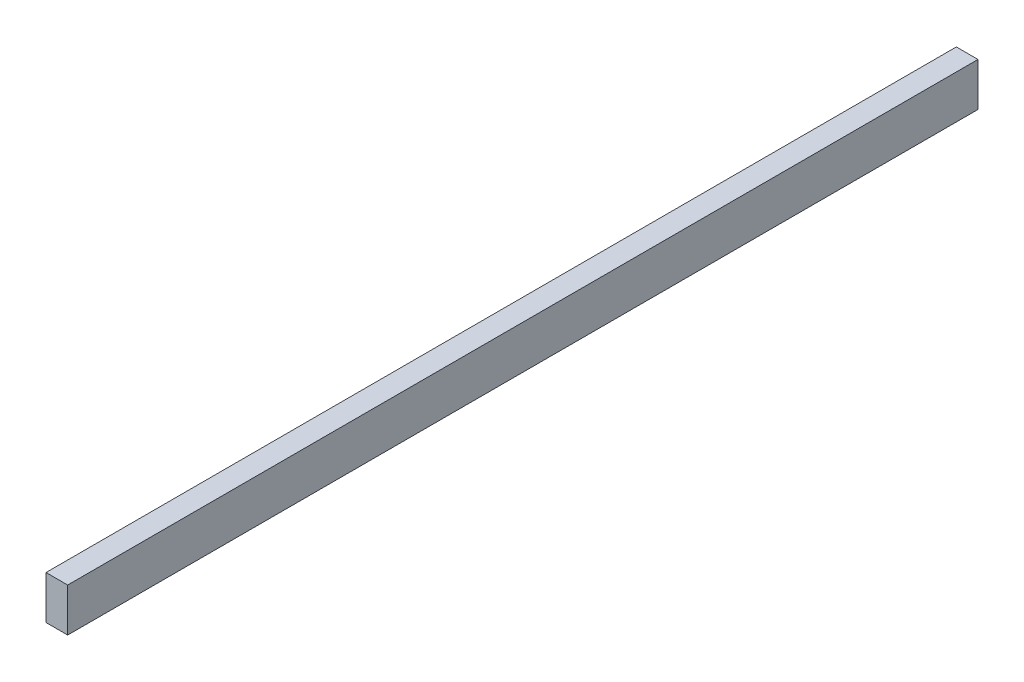
SolidWorks part; units mm, degrees
ref_plane "Front Plane" through (0, 0, 0) normal (0, 0, 1) x (1, 0, 0)
ref_plane "Top Plane" through (0, 0, 0) normal (0, 1, 0) x (1, 0, 0)
ref_plane "Right Plane" through (0, 0, 0) normal (1, 0, 0) x (0, 0, -1)
sketch "Sketch1" plane through (0, 0, 0) normal (0, 0, 1) x (1, 0, 0)
  line L0 (-12.7, 25.4) -> (12.7, 25.4)
  line L1 (-12.7, 25.4) -> (-12.7, -25.4)
  line L2 (-12.7, -25.4) -> (12.7, -25.4)
  line L3 (12.7, 25.4) -> (12.7, -25.4)
  line L4 (-12.7, 25.4) -> (12.7, -25.4) construction
  point P4 (12.0112, 25.4717)
  point P5 (0, 0)
  dimension "D1" = 25.4
  dimension "D2" = 50.8
extrude "Boss-Extrude1" add sketch "Sketch1" along normal blind 1066.8
sketch "Sketch2" plane through (0, 0, 1066.8) normal (0, 0, 1) x (1, 0, 0)
  line L0 (-6.8478, 24.8291) -> (-11.9347, 24.8291)
  line L1 (-11.9347, 24.8291) -> (-11.9347, 19.7422)
  line L2 (9.2759, 0.3342) -> (9.3949, 0.4532)
  line L3 (9.2759, -12.1118) -> (9.2759, 0.3342)
  line L4 (9.3866, -12.2225) -> (9.2759, -12.1118)
  line L5 (9.2433, -12.3658) -> (9.3866, -12.2225)
  line L6 (9.2433, -17.9626) -> (9.2433, -12.3658)
  line L7 (4.6078, -23.9228) -> (4.6078, -22.2178)
  line L8 (-5.1712, -23.9228) -> (4.6078, -23.9228)
  line L9 (-5.1712, -22.2178) -> (-5.1712, -23.9228)
  line L10 (-9.8067, -12.3658) -> (-9.8067, -17.9626)
  line L11 (-9.9337, -12.2388) -> (-9.8067, -12.3658)
  line L12 (-9.8067, -12.1118) -> (-9.9337, -12.2388)
  line L13 (-9.8067, 0.3342) -> (-9.8067, -12.1118)
  line L14 (-9.9337, 0.4612) -> (-9.8067, 0.3342)
  line L15 (-9.8067, 0.5882) -> (-9.9337, 0.4612)
  line L16 (-9.8067, 13.0342) -> (-9.8067, 0.5882)
  line L17 (-9.9174, 13.1449) -> (-9.8067, 13.0342)
  line L18 (-9.7741, 13.2882) -> (-9.9174, 13.1449)
  line L19 (-9.7741, 18.885) -> (-9.7741, 13.2882)
  line L20 (-5.1712, 24.8291) -> (-5.1712, 23.1241)
  line L21 (4.6078, 24.8291) -> (-5.1712, 24.8291)
  line L22 (4.6078, 23.1241) -> (4.6078, 24.8291)
  line L23 (9.1633, 13.1857) -> (9.1633, 18.7825)
  line L24 (9.3021, 13.0443) -> (9.1633, 13.1857)
  line L25 (9.2759, 13.0181) -> (9.3021, 13.0443)
  line L26 (9.2759, 0.5721) -> (9.2759, 13.0181)
  line L27 (9.3949, 0.4532) -> (9.2759, 0.5721)
  arc A0 (4.6078, -22.2178) -> (9.2433, -17.9626) centre (-0.2817, -12.2388) ccw
  arc A1 (-9.8067, -17.9626) -> (-5.1712, -22.2178) centre (-0.2817, -12.2388) ccw
  arc A2 (-5.1712, 23.1241) -> (-9.7741, 18.885) centre (-0.2491, 13.1612) ccw
  arc A3 (9.1633, 18.7825) -> (4.6078, 23.1241) centre (-0.4673, 13.2382) ccw
  arc A4 (-6.1551, 24.1371) -> (-6.8478, 24.8291) centre (-6.8478, 24.1364) ccw
  arc A5 (-6.4908, 23.5446) -> (-6.1551, 24.1371) centre (-6.8446, 24.1364) ccw
  arc A6 (-6.4908, 23.5446) -> (-10.6571, 19.3913) centre (-0.267, 13.1347) ccw
  arc A7 (-11.9347, 19.7422) -> (-10.6571, 19.3913) centre (-11.2477, 19.7422) ccw
  point P44 (-11.9331, 24.8291)
  point P45 (0, 0)
  point P46 (0, 0)
  point P47 (0, 0)
  point P48 (0, 0)
  point P49 (0, 0)
  point P50 (0, 0)
  point P51 (0, 0)
  dimension "D7" = 11.1125
  dimension "D1" = 5.0869
  dimension "D2" = 5.0869
  dimension "D3" = 9.779
  dimension "D4" = 12.446
  dimension "D5" = 12.446
  dimension "D6" = 5.5968
  dimension "D8" = 1.705
  dimension "D9" = 5.5968
  dimension "D11" = 1.705
